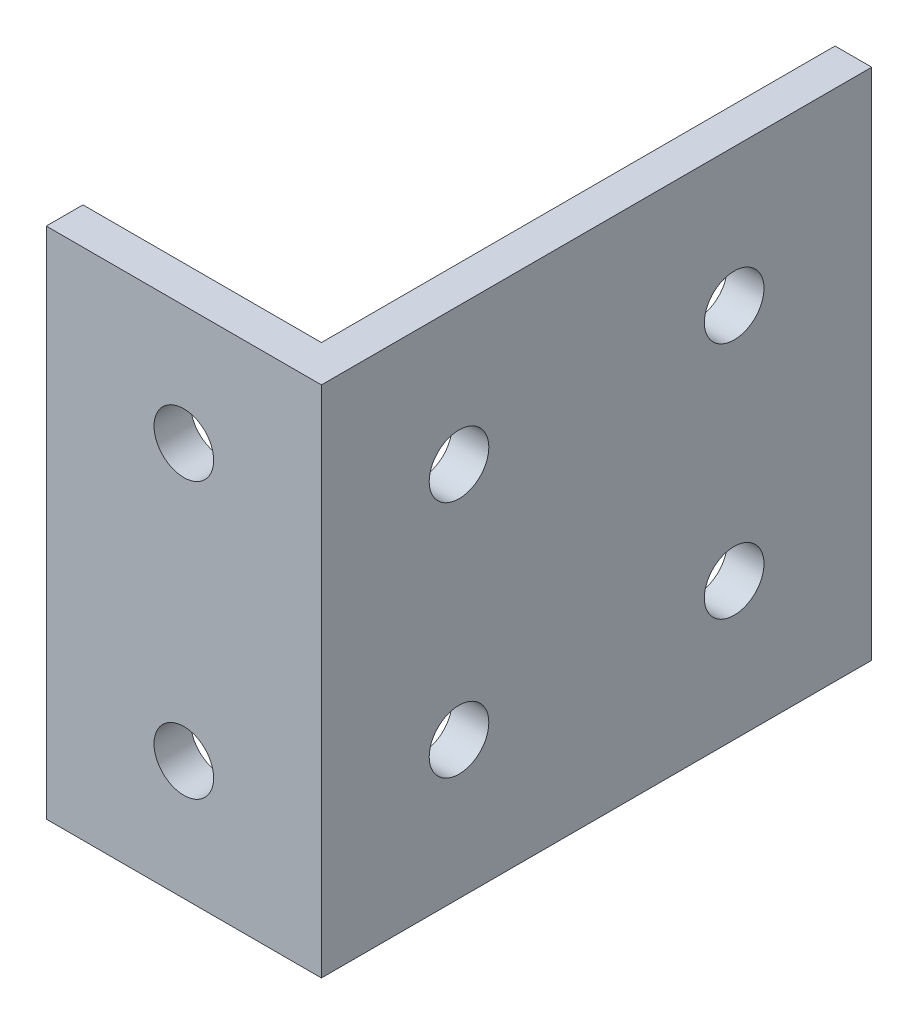
SolidWorks part; units mm, degrees
ref_plane "前视基准面" through (0, 0, 0) normal (0, 0, 1) x (1, 0, 0)
ref_plane "上视基准面" through (0, 0, 0) normal (0, 1, 0) x (1, 0, 0)
ref_plane "右视基准面" through (0, 0, 0) normal (1, 0, 0) x (0, 0, -1)
other "Configuration Table"
sketch "草图1" plane through (0, 0, 0) normal (0, 1, 0) x (1, 0, 0)
  line L0 (0, 0) -> (-30, 0)
  line L1 (-30, 0) -> (-30, 4)
  line L2 (-30, 4) -> (-4, 4)
  line L3 (-4, 4) -> (-4, 60)
  line L4 (-4, 60) -> (0, 60)
  line L5 (0, 60) -> (0, 0)
  dimension "D1" = 30
  dimension "D2" = 60
  dimension "D3" = 4
  dimension "D4" = 4
extrude "凸台-拉伸1" add sketch "草图1" along normal blind 56
sketch "草图2" plane through (0, 0, -4) normal (0, 0, -1) x (-1, 0, 0)
  line L0 (30, 56) -> (30, 0) construction
  line L1 (15, 43) -> (15, 13) construction
  line L2 (15, 28) -> (30, 28) construction
  circle A0 centre (15, 43) radius 3.25
  circle A1 centre (15, 13) radius 3.25
  dimension "D1" = 6.5
  dimension "D2" = 30
  dimension "D3" = 15
extrude "切除-拉伸1" cut sketch "草图2" against normal through all both and the other way through all
sketch "草图3" plane through (0, 0, 0) normal (1, 0, 0) x (0, 0, -1)
  line L0 (0, 28) -> (60, 28) construction
  line L1 (0, 56) -> (0, 0) construction
  line L2 (60, 56) -> (60, 0) construction
  line L3 (0, 56) -> (60, 56) construction
  line L4 (30, 56) -> (30, 0) construction
  line L5 (0, 0) -> (60, 0) construction
  circle A0 centre (15, 41) radius 3.25
  circle A1 centre (15, 15) radius 3.25
  circle A2 centre (45, 15) radius 3.25
  circle A3 centre (45, 41) radius 3.25
  dimension "D1" = 6.5
  dimension "D2" = 15
  dimension "D3" = 15
  dimension "D4" = 26
extrude "切除-拉伸2" cut sketch "草图3" against normal through all both and the other way through all
